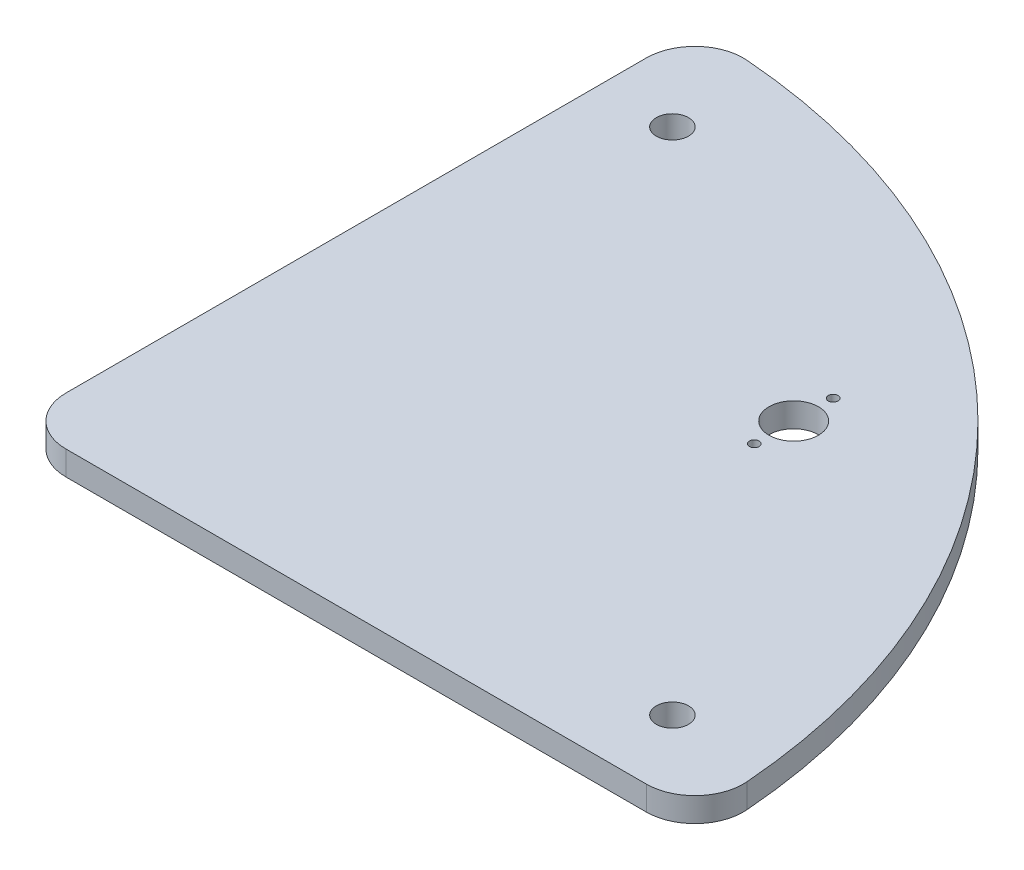
SolidWorks part; units mm, degrees
material "Acrylic (Medium-high impact)"
ref_plane "Front Plane" through (0, 0, 0) normal (0, 0, 1) x (1, 0, 0)
ref_plane "Top Plane" through (0, 0, 0) normal (0, 1, 0) x (1, 0, 0)
ref_plane "Right Plane" through (0, 0, 0) normal (1, 0, 0) x (0, 0, -1)
sketch "Sketch1" plane through (0, 0, 0) normal (0, 1, 0) x (1, 0, 0)
  line L0 (0, 177.8) -> (0, 0)
  line L1 (0, 0) -> (177.8, 0)
  arc A0 (0, 177.8) -> (177.8, 0) centre (0, 0) cw
  dimension "D1" = 177.8
extrude "Boss-Extrude1" add sketch "Sketch1" along normal mid plane 6.35
sketch "Sketch2" plane through (0, 3.175, 0) normal (0, 1, 0) x (1, 0, 0)
  line L0 (101.6, 91.2749) -> (101.6, 111.9251) construction
  line L1 (0, 0) -> (101.6, 0) construction
  line L2 (0, 0) -> (0, 101.6) construction
  line L3 (0, 101.6) -> (101.6, 101.6) construction
  line L4 (101.6, 0) -> (101.6, 101.6) construction
  circle A0 centre (101.6, 101.6) radius 6.477
  circle A1 centre (101.6, 91.2749) radius 1.27
  circle A2 centre (101.6, 111.9251) radius 1.27
  point P10 (101.6, 92.5449)
  point P11 (101.6, 110.6551)
  point P13 (101.6, 101.6)
  dimension "D1" = 12.954
  dimension "D3" = 2.54
  dimension "D2" = 101.6
  dimension "D4" = 10.3251
extrude "Cut-Extrude1" cut sketch "Sketch2" against normal through all
hole_wizard "Q (0.332) Diameter Hole1" positions "Sketch3" profile "Sketch4" hole size "Q" standard "ANSI Inch" end condition through all
sketch "Sketch3" plane through (0, 3.175, 0) normal (0, 1, 0) x (1, 0, 0)
  line L1 (19.05, 152.4) -> (152.4, 152.4) construction
  line L2 (19.05, 152.4) -> (19.05, 19.05) construction
  line L3 (19.05, 19.05) -> (152.4, 19.05) construction
  line L4 (152.4, 152.4) -> (152.4, 19.05) construction
  line L5 (0, 0) -> (177.8, 0) construction
  line L6 (0, 177.8) -> (0, 0) construction
  point P1 (19.05, 152.4)
  point P2 (152.4, 19.05)
  dimension "D1" = 19.05
  dimension "D2" = 19.05
  dimension "D3" = 152.4
sketch "Sketch4" plane through (19.05, 3.175, -152.4) normal (1, 0, 0) x (0, 0, 1)
  line L0 (0, 0) -> (0, 6.35)
  line L1 (0, 6.35) -> (4.2164, 6.35)
  line L2 (4.2164, 6.35) -> (4.2164, 0)
  line L5 (4.2164, 0) -> (0, 0)
  line L11 (0, -6.35) -> (0, 107.95) construction
  dimension "Thru Hole Dia." = 8.4328
  dimension "Thru Hole Depth" = 6.35
fillet "Fillet1" radius 12.7 3 edges at (177.8, 0, 0) (0, 0, 0) (0, 0, -177.8)
